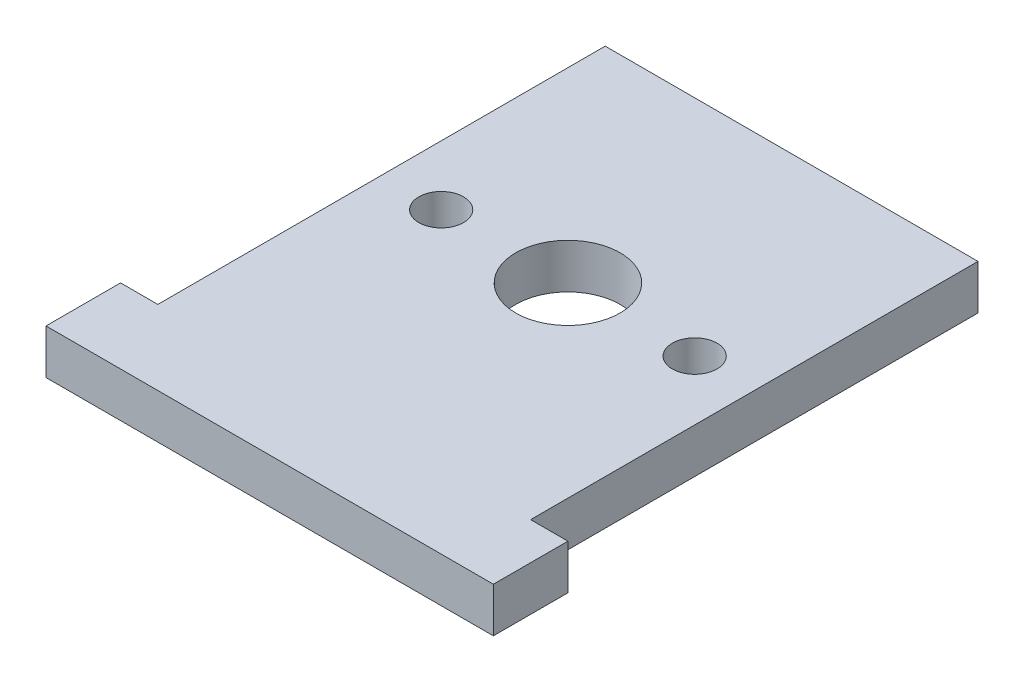
SolidWorks part; units mm, degrees
ref_plane "Front Plane" through (0, 0, 0) normal (0, 0, 1) x (1, 0, 0)
ref_plane "Top Plane" through (0, 0, 0) normal (0, 1, 0) x (1, 0, 0)
ref_plane "Right Plane" through (0, 0, 0) normal (1, 0, 0) x (0, 0, -1)
sketch "Sketch1" plane through (0, 0, 0) normal (0, 1, 0) x (1, 0, 0)
  line L5 (-39.023, 13.2726) -> (-14.023, 13.2726)
  line L6 (-39.023, 13.2726) -> (-39.023, -16.7274)
  line L7 (-39.023, -16.7274) -> (-14.023, -16.7274)
  line L8 (-14.023, 13.2726) -> (-14.023, -16.7274)
  line L9 (-41.523, -16.7274) -> (-11.523, -16.7274)
  line L10 (-41.523, -16.7274) -> (-41.523, -21.7274)
  line L11 (-41.523, -21.7274) -> (-11.523, -21.7274)
  line L12 (-11.523, -16.7274) -> (-11.523, -21.7274)
  line L13 (-22.023, 13.2726) -> (-31.023, 13.2726)
  line L14 (-22.023, 13.2726) -> (-22.023, 43.2726) construction
  line L15 (-22.023, 43.2726) -> (-31.023, 43.2726) construction
  line L16 (-31.023, 13.2726) -> (-31.023, 43.2726) construction
  circle A3 centre (-18.023, -1.7274) radius 1.5
  circle A4 centre (-26.523, -1.7274) radius 3.5
  circle A5 centre (-35.023, -1.7274) radius 1.5
  dimension "D11" = 3
  dimension "D12" = 3
  dimension "D13" = 7
  dimension "D14" = 4
  dimension "D17" = 4
  dimension "D19" = 15
  dimension "D20" = 15
  dimension "D22" = 8.5
  dimension "3" = 30
  dimension "D2" = 2.5
  dimension "D3" = 2.5
  dimension "D4" = 30
  dimension "D5" = 30
  dimension "D6" = 30
  dimension "D7" = 30
  dimension "D8" = 8
  dimension "D9" = 8
  dimension "D10" = 9
  dimension "D15" = 25
  dimension "D16" = 5
  dimension "D18" = 15
  dimension "D21" = 12.5
extrude "Boss-Extrude4" add sketch "Sketch1" along normal blind 3
